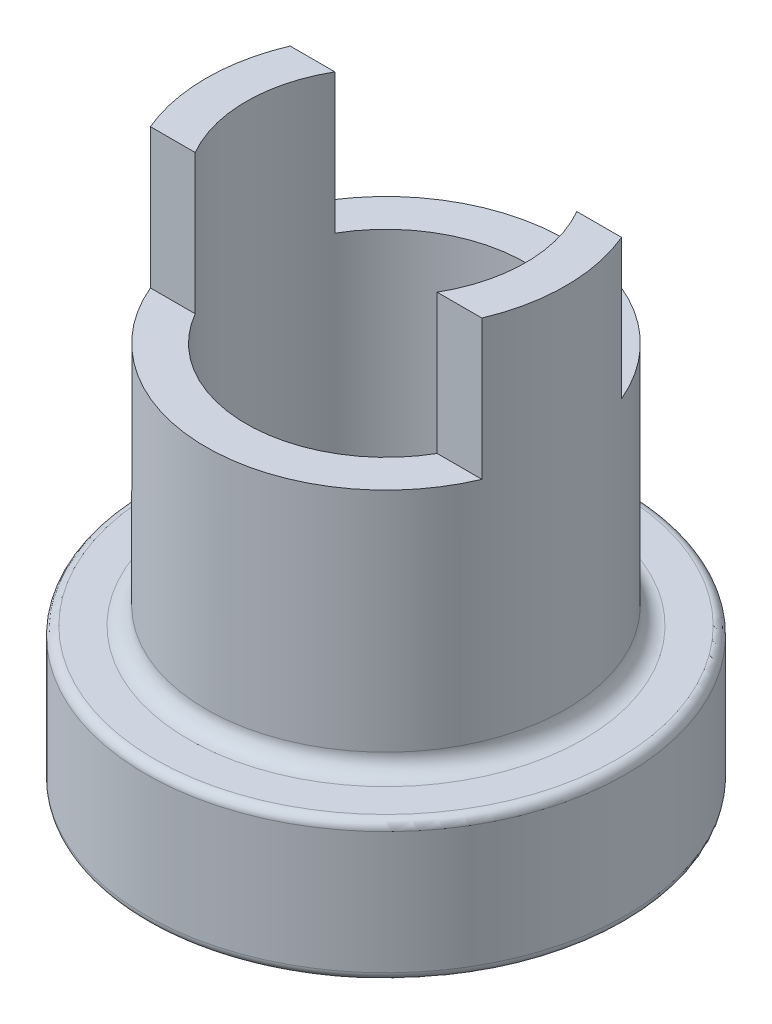
SolidWorks part; units mm, degrees
material "Brass"
ref_plane "Front Plane" through (0, 0, 0) normal (0, 0, 1) x (1, 0, 0)
ref_plane "Top Plane" through (0, 0, 0) normal (0, 1, 0) x (1, 0, 0)
ref_plane "Right Plane" through (0, 0, 0) normal (1, 0, 0) x (0, 0, -1)
sketch "Sketch1" plane through (0, 0, 0) normal (0, 0, 1) x (1, 0, 0)
  line L0 (0, 0) -> (-6.875, 0)
  line L1 (-6.875, 0) -> (-6.875, 4)
  line L2 (-6.875, 4) -> (-5.15, 4)
  line L3 (-5.15, 4) -> (-5.15, 15)
  line L4 (-5.15, 15) -> (0, 15)
  line L5 (0, 15) -> (0, 0)
  dimension "D1" = 5.15
  dimension "D2" = 6.875
  dimension "D3" = 4
  dimension "D4" = 15
revolve "Revolve1" add sketch "Sketch1" angle 360 about L5
sketch "Sketch2" plane through (0, 15, 0) normal (0, 1, 0) x (1, 0, 0)
  circle A0 centre (0, 0) radius 4
extrude "Cut-Extrude1" cut sketch "Sketch2" against normal through all
ref_plane "Plane1" through (5.15, 0, 0) normal (1, 0, 0) x (0, 0, -1)
sketch "Sketch3" plane through (5.15, 0, 0) normal (1, 0, 0) x (0, 0, -1)
  line L0 (5.15, 15) -> (-5.15, 15) construction
  line L1 (-2, 15) -> (-5.15, 15)
  line L2 (-2, 15) -> (-2, 11)
  line L3 (-2, 11) -> (-5.15, 11)
  line L4 (-5.15, 15) -> (-5.15, 11)
  line L5 (-5.15, 15) -> (-5.15, 4) construction
  line L6 (5.15, 4) -> (5.15, 15) construction
  line L7 (2, 15) -> (5.15, 15)
  line L8 (2, 15) -> (2, 11)
  line L9 (2, 11) -> (5.15, 11)
  line L10 (5.15, 15) -> (5.15, 11)
  point P12 (5.15, 10.6196)
  dimension "D1" = 4
  dimension "D2" = 0
  dimension "D3" = 4
extrude "Cut-Extrude2" cut sketch "Sketch3" against normal through all
fillet "Fillet1" radius 0.5 1 edges at (-5.15, 4, 0)
fillet "Fillet2" radius 0.25 2 edges at (-6.875, 0, 0) (-6.875, 4, 0)
chamfer "Chamfer1" distance 0.75 angle 45 1 edges at (-4, 0, 0)
